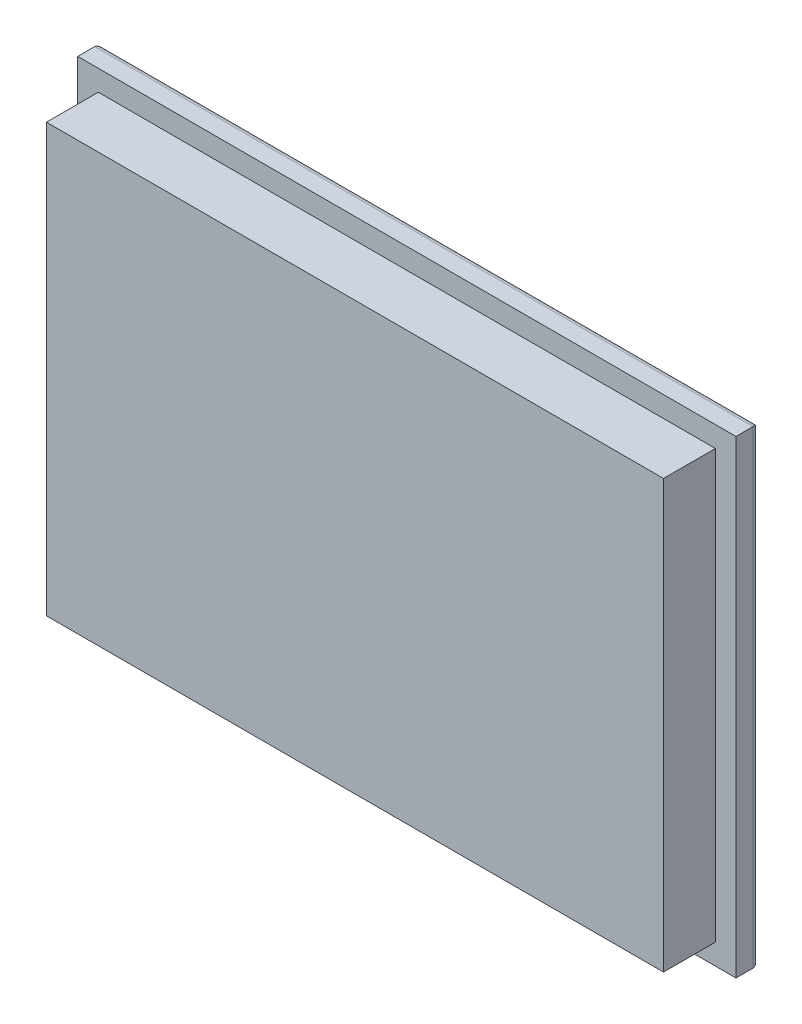
SolidWorks part; units mm, degrees
ref_plane "前视基准面" through (0, 0, 0) normal (0, 0, 1) x (1, 0, 0)
ref_plane "上视基准面" through (0, 0, 0) normal (0, 1, 0) x (1, 0, 0)
ref_plane "右视基准面" through (0, 0, 0) normal (1, 0, 0) x (0, 0, -1)
sketch "草图1" plane through (0, 0, 0) normal (0, 0, 1) x (1, 0, 0)
  line L0 (0, 154.6511) -> (0, -203.0003) construction
  line L1 (-104.7, 74.6) -> (104.7, 74.6)
  line L2 (-104.7, 74.6) -> (-104.7, -74.6)
  line L3 (-104.7, -74.6) -> (104.7, -74.6)
  line L4 (104.7, 74.6) -> (104.7, -74.6)
  line L5 (-185.78, 0) -> (224.8568, 0) construction
  dimension "D1" = 209.4
  dimension "D2" = 149.2
extrude "凸台-拉伸1" add sketch "草图1" along normal blind 7.4
sketch "草图2" plane through (0, 0, 7.4) normal (0, 0, 1) x (1, 0, 0)
  line L0 (0, 84.9806) -> (0, -95.3538) construction
  line L1 (-98.15, 68) -> (98.15, 68)
  line L2 (-98.15, 68) -> (-98.15, -68)
  line L3 (-98.15, -68) -> (98.15, -68)
  line L4 (98.15, 68) -> (98.15, -68)
  line L5 (-113.7064, 0) -> (124.8776, 0) construction
  dimension "D1" = 196.3
  dimension "D2" = 136
extrude "凸台-拉伸2" add sketch "草图2" along normal blind 16.5
ref_plane "基准面1" through (1.2, 0, 0) normal (1, 0, 0) x (0, 0, -1)
ref_plane "基准面2" through (0, 6.2, 0) normal (0, 1, 0) x (1, 0, 0)
sketch "草图4" plane through (0, 0, 0) normal (0, 0, -1) x (-1, 0, 0)
  line L0 (-84.9939, 6.2) -> (87.042, 6.2) construction
  line L1 (-78.25, 49.15) -> (75.85, 49.15)
  line L2 (-78.25, 49.15) -> (-78.25, -36.75)
  line L3 (-78.25, -36.75) -> (75.85, -36.75)
  line L4 (75.85, 49.15) -> (75.85, -36.75)
  line L5 (4.07, 6.2) -> (-4.07, 6.2) construction
  line L6 (-1.2, 64.5134) -> (-1.2, -65.9763) construction
  line L7 (-1.2, 4.07) -> (-1.2, -4.07) construction
  dimension "D1" = 154.1
  dimension "D2" = 85.9
extrude "切除-拉伸1" cut sketch "草图4" against normal blind 1.5
fillet "圆角1" radius 2 4 edges at (-104.7, 0, 0) (0, -74.6, 0) (104.7, 0, 0) (0, 74.6, 0)
sketch "草图5" plane through (0, 0, 0) normal (0, 0, -1) x (-1, 0, 0)
  line L0 (-127.7103, 0) -> (121.2736, 0) construction
  line L1 (-99.7, 69.6) -> (99.7, 69.6)
  line L2 (-99.7, 69.6) -> (-99.7, -69.6)
  line L3 (-99.7, -69.6) -> (99.7, -69.6)
  line L4 (99.7, 69.6) -> (99.7, -69.6)
  line L5 (0, 87.3345) -> (0, -90.8455) construction
  line L6 (-104.7, -74.6) -> (-104.7, 74.6) construction
  line L7 (104.7, -74.6) -> (-104.7, -74.6) construction
  dimension "D1" = 5
  dimension "D2" = 5
extrude "切除-拉伸2" cut sketch "草图5" against normal blind 0.5
fillet "圆角2" radius 3 4 edges at (-99.7, -69.6, 0.25) (-99.7, 69.6, 0.25) (99.7, 69.6, 0.25) (99.7, -69.6, 0.25)
sketch "草图6" plane through (0, 0, 1.5) normal (0, 0, -1) x (-1, 0, 0)
  line L0 (-78.25, 49.15) -> (75.85, 49.15) construction
  line L1 (-78.25, 49.15) -> (-78.25, -36.75) construction
  line L2 (75.85, -36.75) -> (-78.25, -36.75) construction
  line L3 (75.85, -36.75) -> (75.85, 49.15) construction
  line L4 (-78.25, 49.15) -> (75.85, 49.15)
  line L5 (-78.25, 49.15) -> (-78.25, -36.75)
  line L6 (75.85, -36.75) -> (-78.25, -36.75)
  line L7 (75.85, -36.75) -> (75.85, 49.15)
extrude "凸台-拉伸3" [suppressed] add sketch "草图6" along normal blind 3
